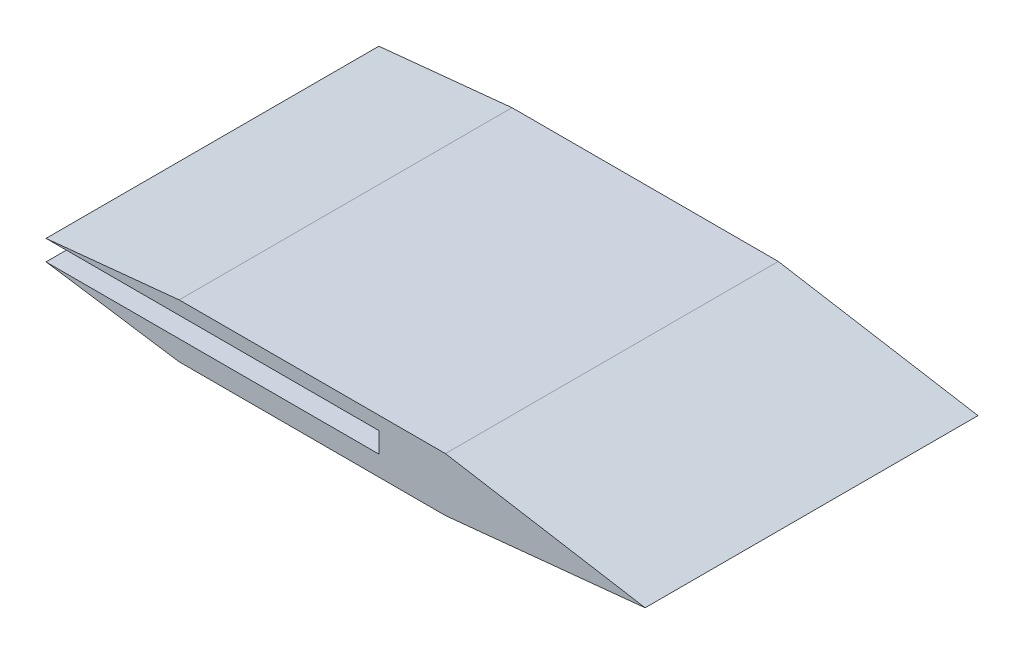
SolidWorks part; units mm, degrees
ref_plane "Přední rovina" through (0, 0, 0) normal (0, 0, 1) x (1, 0, 0)
ref_plane "Horní rovina" through (0, 0, 0) normal (0, 1, 0) x (1, 0, 0)
ref_plane "Pravá rovina" through (0, 0, 0) normal (1, 0, 0) x (0, 0, -1)
sketch "Skica1" plane through (0, 0, 0) normal (0, 0, 1) x (1, 0, 0)
  line L0 (0, 0) -> (20, 2)
  line L1 (20, 2) -> (60, 2)
  line L2 (60, 2) -> (90, -3.06)
  line L3 (90, -3.06) -> (60, -6.06)
  line L6 (0, -3.06) -> (50, -3.06)
  line L7 (50, -3.06) -> (50, 0)
  line L8 (50, 0) -> (0, 0)
  line L9 (50, -3.06) -> (113.4883, -3.06) construction
  line L10 (60, -6.06) -> (20, -6.06)
  line L11 (20, -6.06) -> (0, -3.06)
  dimension "D1" = 3.06
  dimension "D2" = 3
  dimension "D3" = 2
  dimension "D4" = 20
  dimension "D5" = 20
  dimension "D6" = 50
  dimension "D7" = 50
  dimension "D8" = 40
  dimension "D9" = 40
extrude "Přidat vysunutím1" add sketch "Skica1" along normal blind 50
